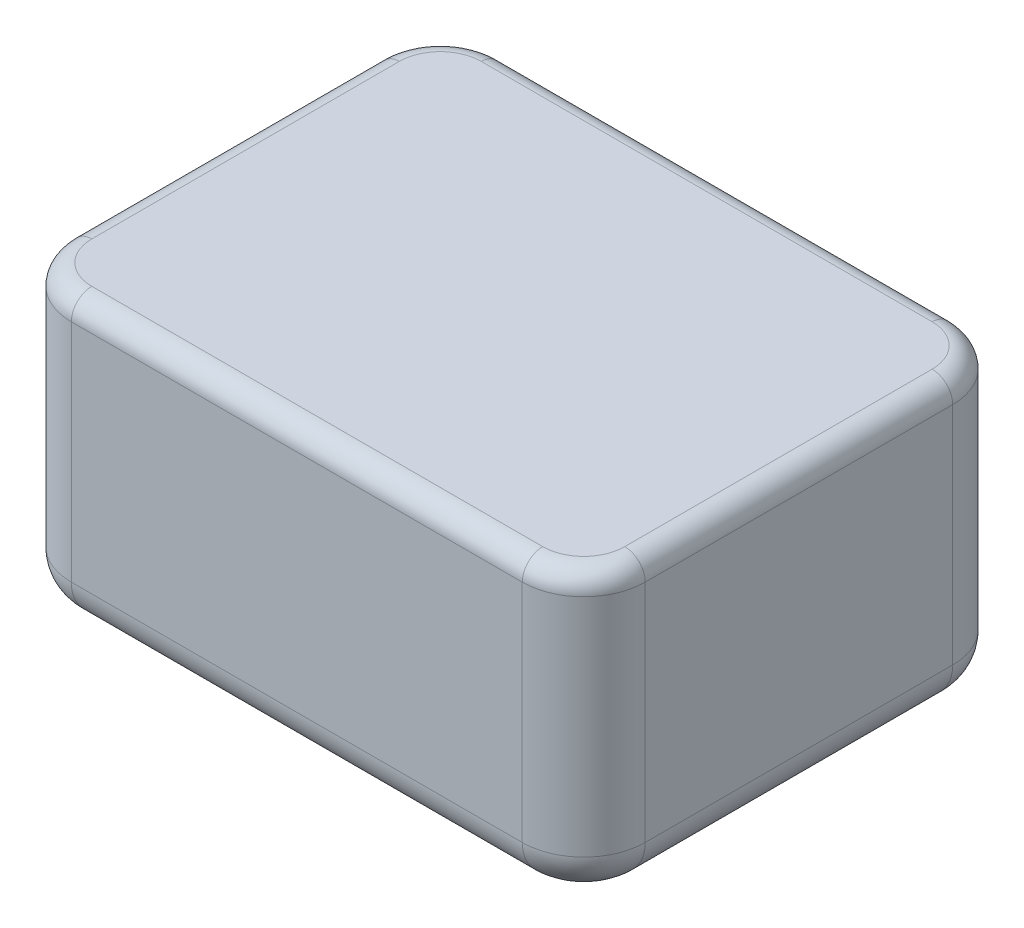
SolidWorks part; units mm, degrees
ref_plane "Front" through (0, 0, 0) normal (0, 0, 1) x (1, 0, 0)
ref_plane "Top" through (0, 0, 0) normal (0, 1, 0) x (1, 0, 0)
ref_plane "Right" through (0, 0, 0) normal (1, 0, 0) x (0, 0, -1)
sketch "草图1" plane through (0, 0, 0) normal (0, 1, 0) x (1, 0, 0)
  line L1 (70, -52.5) -> (-70, -52.5)
  line L2 (70, -52.5) -> (70, 52.5)
  line L3 (70, 52.5) -> (-70, 52.5)
  line L4 (-70, -52.5) -> (-70, 52.5)
  line L5 (70, -52.5) -> (-70, 52.5) construction
  line L6 (70, 52.5) -> (-70, -52.5) construction
  point P0 (0, 0)
  dimension "D1" = 140
  dimension "D2" = 105
extrude "凸台-拉伸1" add sketch "草图1" along normal blind 70
fillet "圆角1" radius 15 4 edges at (-70, 35, -52.5) (70, 35, -52.5) (70, 35, 52.5) (-70, 35, 52.5)
fillet "圆角2" radius 10 8 edges at (65.6066, 0, -48.1066) (65.6066, 0, 48.1066) (-65.6066, 0, 48.1066) (-65.6066, 0, -48.1066) (-70, 0, 0) (0, 0, 52.5) (70, 0, 0) (0, 0, -52.5)
fillet "圆角3" radius 5 8 edges at (65.6066, 70, -48.1066) (70, 70, 0) (65.6066, 70, 48.1066) (0, 70, 52.5) (-65.6066, 70, 48.1066) (-70, 70, 0) (-65.6066, 70, -48.1066) (0, 70, -52.5)
